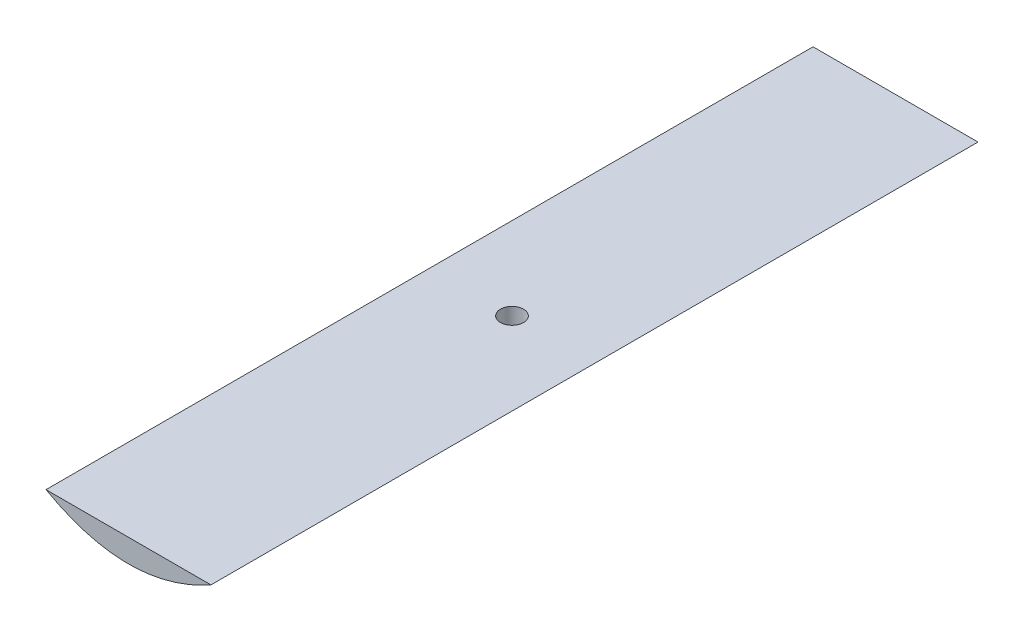
SolidWorks part; units mm, degrees
ref_plane "Front Plane" through (0, 0, 0) normal (0, 0, 1) x (1, 0, 0)
ref_plane "Top Plane" through (0, 0, 0) normal (0, 1, 0) x (1, 0, 0)
ref_plane "Right Plane" through (0, 0, 0) normal (1, 0, 0) x (0, 0, -1)
sketch "Sketch2" plane through (0, 0, 0) normal (0, 0, 1) x (1, 0, 0)
  line L0 (-127, 127) -> (127, 127)
  spline S0 degree 2 poles (-143.0272, 161.0769) (0, -161.0769) (143.0272, 161.0769) knots 0 0 0 1 1 1 construction
  spline S1 degree 2 poles (-127, 127) (0, -127) (127, 127) knots 0.056028 0.056028 0.056028 0.943972 0.943972 0.943972
extrude "Boss-Extrude2" add sketch "Sketch2" along normal blind 331.382
sketch "Sketch3" plane through (0, 127, 0) normal (0, 1, 0) x (1, 0, 0)
  line L0 (0, -309.5365) -> (0, 0) construction
  line L9 (-127, -165.691) -> (127, -165.691) construction
  line L10 (-127, -331.382) -> (-127, 0) construction
  line L11 (127, -331.382) -> (127, 0) construction
  circle A0 centre (0, -165.691) radius 5
  dimension "D3" = 10
extrude "Cut-Extrude2" cut sketch "Sketch3" against normal through all
sketch "Sketch4" plane through (0, 0, 0) normal (0, 0, -1) x (-1, 0, 0)
  line L1 (-120, 111.6) -> (120, 111.6)
  line L2 (-120, 111.6) -> (-120, 0)
  line L3 (-120, 0) -> (120, 0)
  line L4 (120, 111.6) -> (120, 0)
  dimension "D1" = 111.6
  dimension "D2" = 240
extrude "Cut-Extrude3" [suppressed] cut sketch "Sketch4" against normal through all
sketch "Sketch5" plane through (0, 0, 331.382) normal (0, 0, 1) x (1, 0, 0)
  line L0 (0, 0) -> (0, 10) construction
  line L1 (-130, 130) -> (130, 130)
  line L2 (-130, 130) -> (-130, 10)
  line L3 (-130, 10) -> (130, 10)
  line L4 (130, 130) -> (130, 10)
  dimension "D1" = 10
  dimension "D2" = 260
  dimension "D3" = 120
extrude "Cut-Extrude4" cut sketch "Sketch5" against normal through all
